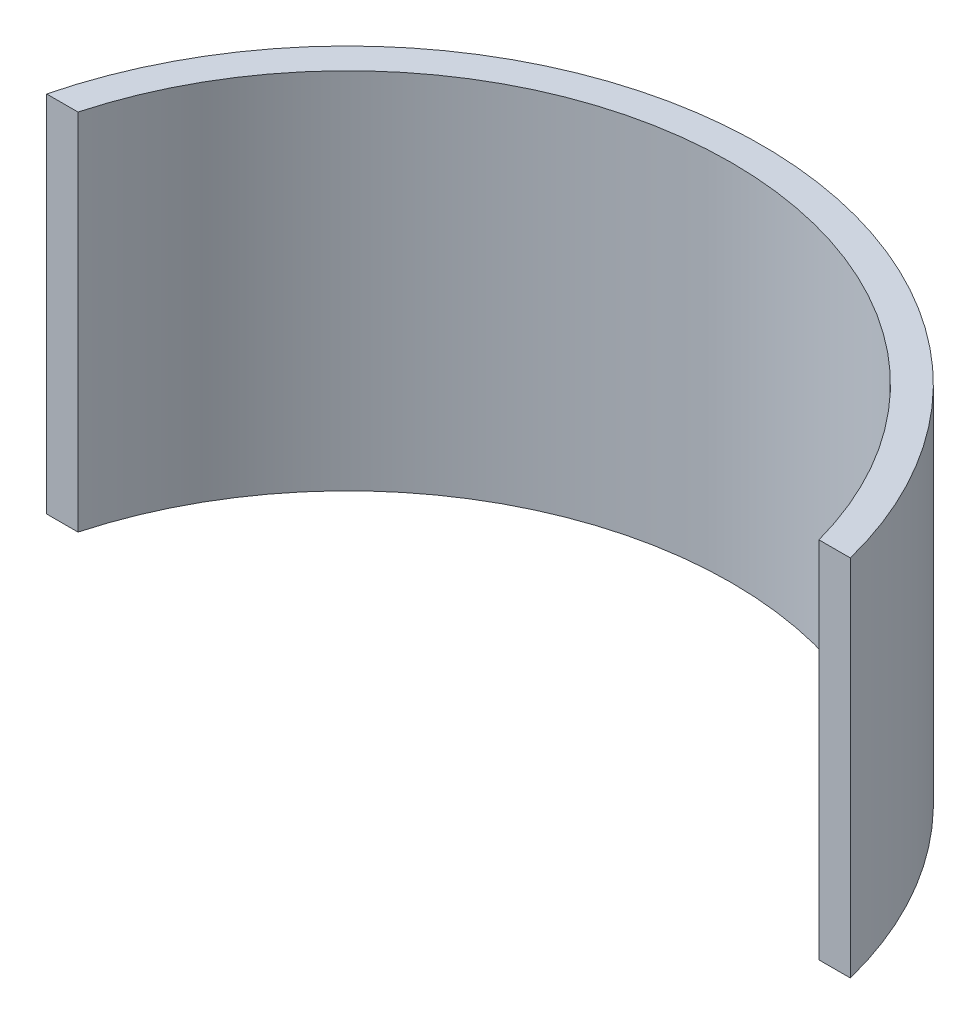
SolidWorks part; units mm, degrees
ref_plane "Płaszczyzna przednia" through (0, 0, 0) normal (0, 0, 1) x (1, 0, 0)
ref_plane "Płaszczyzna górna" through (0, 0, 0) normal (0, 1, 0) x (1, 0, 0)
ref_plane "Płaszczyzna prawa" through (0, 0, 0) normal (1, 0, 0) x (0, 0, -1)
sketch "Sketch1" plane through (0, 0, 0) normal (0, 1, 0) x (1, 0, 0)
  line L0 (-19.8809, 5) -> (-18.3303, 5)
  line L1 (18.3303, 5) -> (19.8809, 5)
  arc A0 (19.3649, 5) -> (-19.3649, 5) centre (0, 0) ccw construction
  arc A1 (19.8809, 5) -> (-19.8809, 5) centre (0, 0) ccw
  arc A2 (18.3303, 5) -> (-18.3303, 5) centre (0, 0) ccw
  circle A3 centre (0, 0) radius 20.5 construction
  circle A4 centre (0, 0) radius 20 construction
  circle A5 centre (0, 0) radius 19 construction
  dimension "D1" = 40
  dimension "D4" = 5
  dimension "D2" = 0.5
  dimension "D3" = 1
extrude "Boss-Extrude1" add sketch "Sketch1" along normal blind 18
